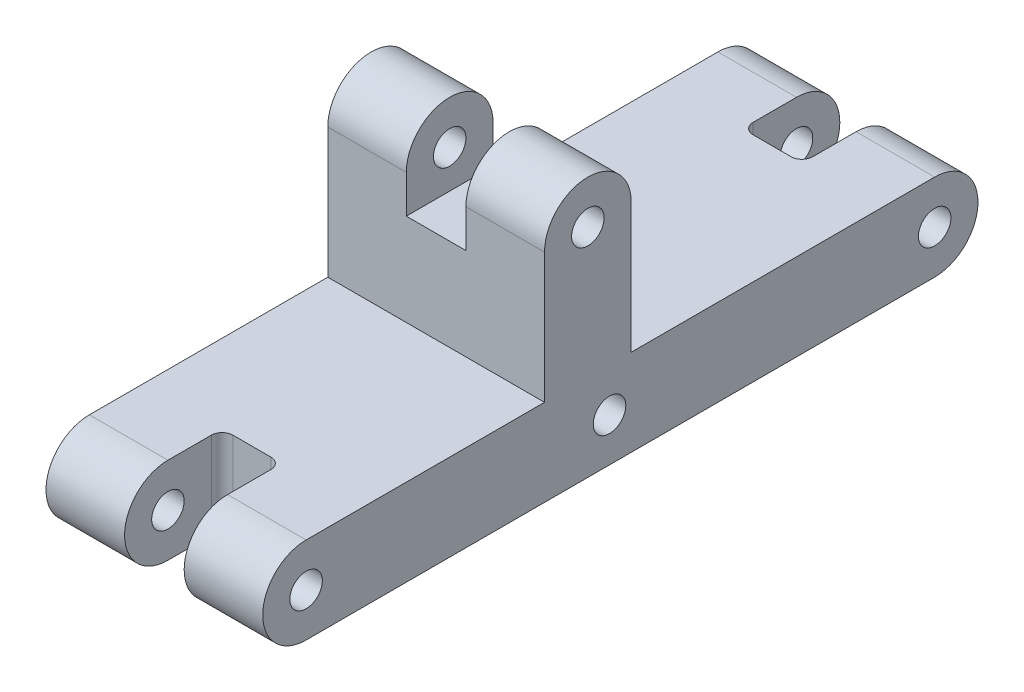
SolidWorks part; units mm, degrees
ref_plane "Alzado" through (0, 0, 0) normal (0, 0, 1) x (1, 0, 0)
ref_plane "Planta" through (0, 0, 0) normal (0, 1, 0) x (1, 0, 0)
ref_plane "Vista lateral" through (0, 0, 0) normal (1, 0, 0) x (0, 0, -1)
sketch "Croquis1" plane through (0, 0, 0) normal (1, 0, 0) x (0, 0, -1)
  line L0 (-15, 0) -> (15, 0) construction
  line L1 (-15, 4) -> (-21, 4) construction
  line L2 (-15, -4) -> (15, -4)
  line L3 (-13, 4) -> (15, 4)
  line L5 (-21, 4) -> (-21, 16)
  line L6 (-21, 16) -> (-13, 16) construction
  line L7 (-13, 4) -> (-13, 16)
  line L8 (-21, 4) -> (-43, 4)
  line L9 (-15, -4) -> (-43, -4)
  line L10 (-43, 4) -> (-43, -4) construction
  arc A0 (-15, 4) -> (-15, -4) centre (-15, 0) ccw construction
  arc A1 (15, -4) -> (15, 4) centre (15, 0) ccw
  circle A2 centre (15, 0) radius 1.5
  arc A3 (-13, 16) -> (-21, 16) centre (-17, 16) ccw
  circle A4 centre (-17, 16) radius 1.5
  circle A5 centre (-15, 0) radius 1.5
  arc A6 (-43, 4) -> (-43, -4) centre (-43, 0) ccw
  circle A7 centre (-43, 0) radius 1.5
  point P3 (0, 0)
  point P20 (-15, 4)
  point P21 (0, 0)
  dimension "D2" = 4
  dimension "D3" = 3
  dimension "D4" = 4
  dimension "D7" = 28
  dimension "D1" = 30
  dimension "D5" = 28
  dimension "D6" = 12
extrude "Saliente-Extruir1" add sketch "Croquis1" along normal mid plane 20
sketch "Croquis2" plane through (0, 0, 0) normal (1, 0, 0) x (0, 0, -1)
  line L0 (-21, 16) -> (-21, 4) construction
  line L1 (-21, 12.5) -> (-13, 12.5)
  line L2 (-21, 12.5) -> (-21, 20)
  line L3 (-21, 20) -> (-13, 20)
  line L4 (-13, 12.5) -> (-13, 20)
  line L5 (-13, 4) -> (-13, 16) construction
  line L11 (-43, -4) -> (15, -4) construction
  line L12 (15, 4) -> (-13, 4) construction
  line L13 (10, 4) -> (19, 4)
  line L14 (10, 4) -> (10, -4)
  line L15 (10, -4) -> (19, -4)
  line L16 (19, 4) -> (19, -4)
  line L18 (-38, 4) -> (-47, 4)
  line L19 (-38, 4) -> (-38, -4)
  line L20 (-38, -4) -> (-47, -4)
  line L21 (-47, 4) -> (-47, -4)
  line L22 (-43, -4) -> (15, -4) construction
  line L23 (-21, 4) -> (-43, 4) construction
  arc A0 (-13, 16) -> (-21, 16) centre (-17, 16) ccw construction
  arc A2 (15, -4) -> (15, 4) centre (15, 0) ccw construction
  arc A5 (-43, 4) -> (-43, -4) centre (-43, 0) ccw construction
  point P11 (0, 0)
  dimension "D5" = 9
  dimension "D1" = 7.5
  dimension "D3" = 9
extrude "Cortar-Extruir1" cut sketch "Croquis2" against normal mid plane 5.5
fillet "Redondeo1" radius 1 4 edges at (2.75, 0, 38) (-2.75, 0, 38) (2.75, 0, -10) (-2.75, 0, -10)
